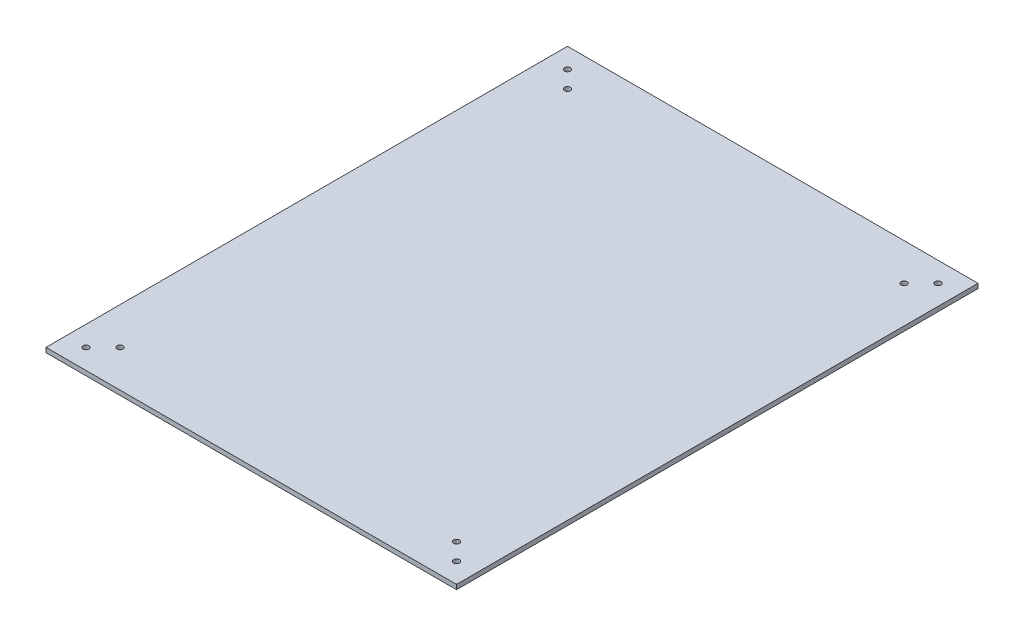
SolidWorks part; units mm, degrees
ref_plane "Front Plane" through (0, 0, 0) normal (0, 0, 1) x (1, 0, 0)
ref_plane "Top Plane" through (0, 0, 0) normal (0, 1, 0) x (1, 0, 0)
ref_plane "Right Plane" through (0, 0, 0) normal (1, 0, 0) x (0, 0, -1)
sketch "Sketch1" plane through (0, 0, 0) normal (0, 1, 0) x (1, 0, 0)
  line L0 (-91, 121) -> (-91, -121) construction
  line L1 (-111, 141) -> (111, 141)
  line L2 (-111, 141) -> (-111, -141)
  line L3 (-111, -141) -> (111, -141)
  line L4 (111, 141) -> (111, -141)
  line L5 (-91, -121) -> (91, -121) construction
  line L6 (91, 121) -> (91, -121) construction
  line L7 (-91, 121) -> (91, 121) construction
  circle A0 centre (-100.182, 130.182) radius 1.6
  circle A1 centre (100.182, 130.182) radius 1.6
  circle A2 centre (-100.182, -130.182) radius 1.6
  circle A3 centre (100.182, -130.182) radius 1.6
  circle A4 centre (-91, 121) radius 1.6
  circle A5 centre (91, 121) radius 1.6
  circle A6 centre (-91, -121) radius 1.6
  circle A7 centre (91, -121) radius 1.6
extrude "Boss-Extrude1" add sketch "Sketch1" along normal blind 2.5
